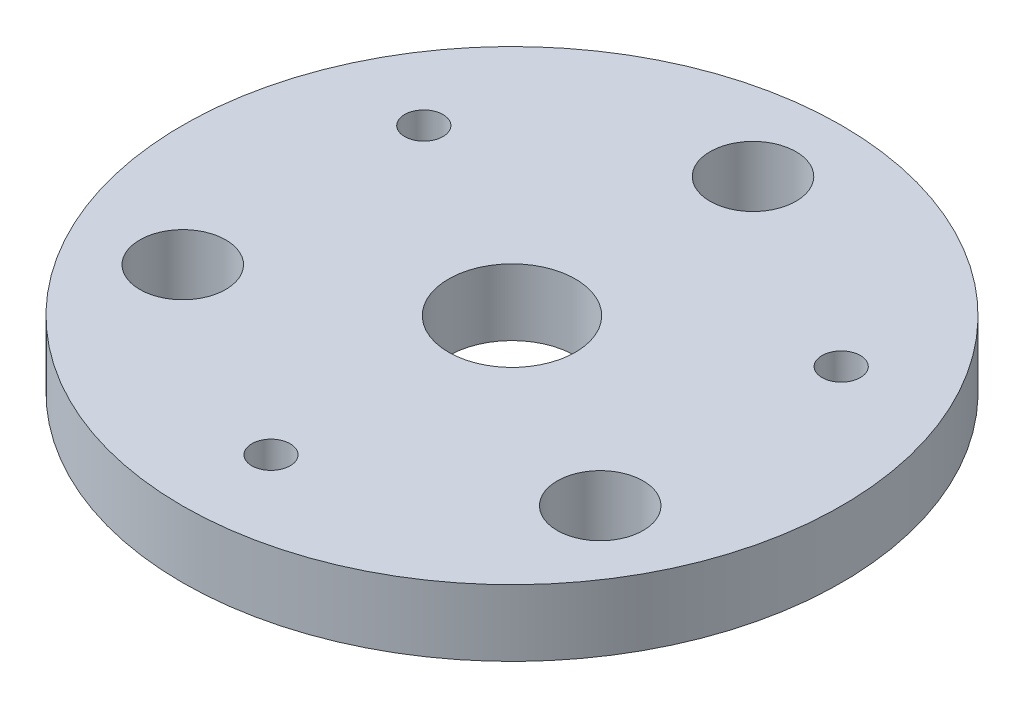
SolidWorks part; units mm, degrees
ref_plane "Front Plane" through (0, 0, 0) normal (0, 0, 1) x (1, 0, 0)
ref_plane "Top Plane" through (0, 0, 0) normal (0, 1, 0) x (1, 0, 0)
ref_plane "Right Plane" through (0, 0, 0) normal (1, 0, 0) x (0, 0, -1)
sketch "Sketch1" plane through (0, 0, 0) normal (0, 1, 0) x (1, 0, 0)
  circle A0 centre (0, 0) radius 38.6524
  circle A1 centre (0, 0) radius 7.4422
  dimension "D1" = 77.3049
  dimension "D2" = 14.8844
extrude "Boss-Extrude1" add sketch "Sketch1" along normal mid plane 7.7978
hole_wizard "3/8 Clearance Hole1" positions "Sketch3" profile "Sketch2" hole size "3/8" standard "ANSI Inch" end condition through all
sketch "Sketch3" plane through (0, 3.8989, 0) normal (0, 1, 0) x (1, 0, 0)
  line L2 (0, 28.2662) -> (24.4793, -14.1331) construction
  line L4 (0, 28.2662) -> (0, -28.2662) construction
  circle A0 centre (0, 0) radius 28.2662 construction
  point P0 (0, 28.2662)
  point P6 (24.4793, -14.1331)
  point P7 (-24.4793, -14.1331)
  dimension "D2" = 48.9585
  dimension "D1" = 3
sketch "Sketch2" plane through (0, 3.8989, -28.2662) normal (1, 0, 0) x (0, 0, 1)
  line L0 (0, 0) -> (0, 7.7978)
  line L1 (0, 7.7978) -> (5.0419, 7.7978)
  line L2 (5.0419, 7.7978) -> (5.0419, 0)
  line L5 (5.0419, 0) -> (0, 0)
  line L11 (0, -6.35) -> (0, 107.95) construction
  dimension "Thru Hole Dia." = 10.0838
  dimension "Thru Hole Depth" = 7.7978
hole_wizard "#8 Clearance Hole1" positions "Sketch5" profile "Sketch4" hole size "#8" standard "ANSI Inch" end condition through all
sketch "Sketch5" plane through (0, 3.8989, 0) normal (0, 1, 0) x (1, 0, 0)
  line L0 (0, -28.2662) -> (0, 28.2662) construction
  circle A1 centre (0, 0) radius 28.2662 construction
  point P0 (24.4793, 14.1331)
  point P13 (0, -28.2662)
  point P14 (-24.4792, 14.1331)
  dimension "D1" = 3
sketch "Sketch4" plane through (24.4793, 3.8989, -14.1331) normal (1, 0, 0) x (0, 0, 1)
  line L0 (0, 0) -> (0, 7.7978)
  line L1 (0, 7.7978) -> (2.2479, 7.7978)
  line L2 (2.2479, 7.7978) -> (2.2479, 0)
  line L5 (2.2479, 0) -> (0, 0)
  line L11 (0, -6.35) -> (0, 107.95) construction
  dimension "Thru Hole Dia." = 4.4958
  dimension "Thru Hole Depth" = 7.7978
